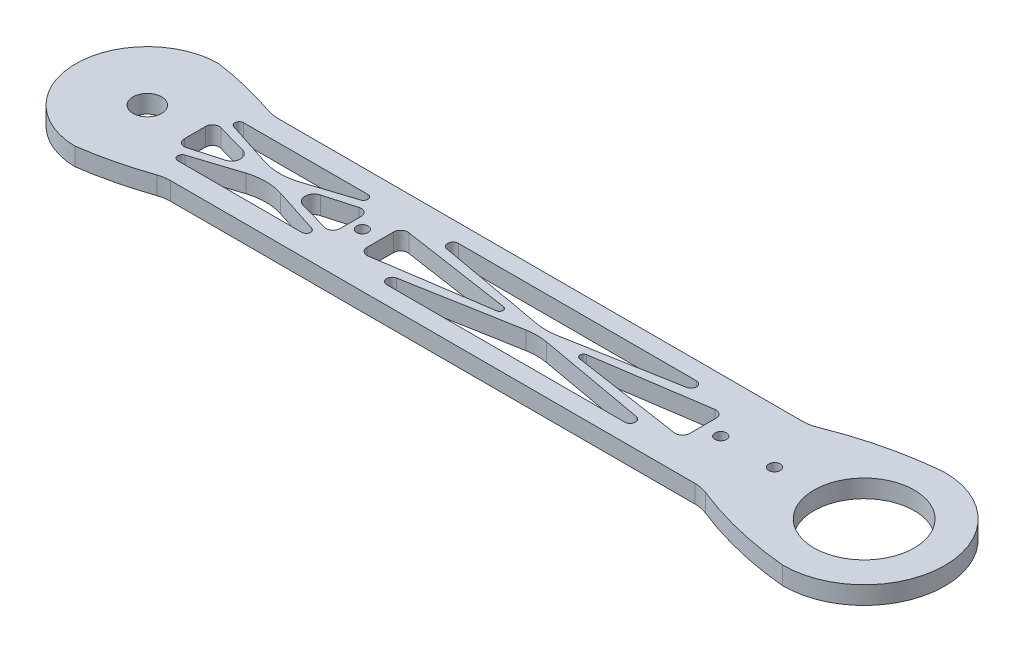
SolidWorks part; units mm, degrees
material "Thornel Mat VMA"
ref_plane "前视基准面" through (0, 0, 0) normal (0, 0, 1) x (1, 0, 0)
ref_plane "上视基准面" through (0, 0, 0) normal (0, 1, 0) x (1, 0, 0)
ref_plane "右视基准面" through (0, 0, 0) normal (1, 0, 0) x (0, 0, -1)
sketch "草图1" plane through (0, 0, 0) normal (0, 1, 0) x (1, 0, 0)
  line L0 (-0.25, 19.9984) -> (199.7188, 22.4982)
  line L5 (300, 0) -> (-49700, 0) construction
  line L6 (-0.25, -19.9984) -> (199.7188, -22.4982)
  arc A0 (-0.25, 19.9984) -> (-0.25, -19.9984) centre (0, 0) ccw
  arc A1 (199.7188, -22.4982) -> (199.7188, 22.4982) centre (200, 0) ccw
  point P0 (0, 0)
  dimension "D1" = 40
  dimension "D2" = 45
  dimension "D3" = 200
extrude "凸台-拉伸1" add sketch "草图1" along normal blind 5
sketch "草图2" plane through (0, 5, 0) normal (0, 1, 0) x (1, 0, 0)
  circle A0 centre (0, 0) radius 4
  dimension "D1" = 8
extrude "切除-拉伸1" cut sketch "草图2" against normal blind 6
sketch "草图3" plane through (0, 5, 0) normal (0, 1, 0) x (1, 0, 0)
  circle A0 centre (200, 0) radius 14
  dimension "D1" = 28
extrude "切除-拉伸2" cut sketch "草图3" against normal blind 10
sketch "草图4" plane through (0, 5, 0) normal (0, 1, 0) x (1, 0, 0)
  line L0 (0, 0) -> (0, 50000) construction
  circle A0 centre (0, 0) radius 12 construction
  circle A1 centre (0, 12) radius 2.1
  circle A2 centre (10.3923, 6) radius 2.1
  circle A3 centre (10.3923, -6) radius 2.1
  circle A4 centre (0, -12) radius 2.1
  circle A5 centre (-10.3923, -6) radius 2.1
  circle A6 centre (-10.3923, 6) radius 2.1
  point P15 (0, 0)
  point P27 (0, 0)
  dimension "D1" = 24
  dimension "D2" = 4.2
  dimension "D3" = 6
sketch "草图6" plane through (0, 5, 0) normal (0, 1, 0) x (1, 0, 0)
  line L0 (60, 15) -> (160.4981, 9.9876)
  line L1 (60, -15) -> (160.4981, -9.9876)
  arc A0 (60, 15) -> (60, -15) centre (60, 0) ccw
  arc A1 (160.4981, -9.9876) -> (160.4981, 9.9876) centre (160, 0) ccw
  dimension "D3" = 30
  dimension "D4" = 20
  dimension "D1" = 100
  dimension "D2" = 60
sketch "草图8" plane through (0, 5, 0) normal (0, 1, 0) x (1, 0, 0)
  line L0 (-0.25, 11.9978) -> (199.7188, 14.4976) construction
  line L1 (199.7188, 22.4982) -> (-0.25, 19.9984) construction
  line L2 (0, 0) -> (50000, 0) construction
  circle A0 centre (65, 12.8135) radius 1.6
  circle A2 centre (114.8261, 8.6468) radius 1.6
  circle A3 centre (164.6522, 4.4802) radius 1.6
  circle A6 centre (164.6522, -4.4802) radius 1.6
  circle A7 centre (114.8261, -8.6468) radius 1.6
  circle A8 centre (65, -12.8135) radius 1.6
  dimension "D2" = 3.2
  dimension "D1" = 8
  dimension "D3" = 65
  dimension "D4" = 3
  dimension "D5" = 50
sketch "草图10" plane through (0, 5, 0) normal (0, 1, 0) x (1, 0, 0)
  line L1 (19.75, 15) -> (169.7188, 15)
  line L2 (19.75, 15) -> (19.75, -15) construction
  line L3 (19.75, -15) -> (169.7188, -15)
  line L4 (169.7188, 15) -> (169.7188, -15) construction
  line L5 (19.75, 15) -> (169.7188, -15) construction
  line L6 (19.75, -15) -> (169.7188, 15) construction
  line L8 (-0.25, 19.9984) -> (199.7188, 22.4982)
  line L9 (-0.25, -19.9984) -> (199.7188, -22.4982)
  arc A0 (-0.25, 19.9984) -> (19.75, 15) centre (-14.3673, -79.0001) cw
  arc A1 (-0.25, -19.9984) -> (19.75, -15) centre (-14.3673, 79.0001) ccw
  arc A2 (199.7188, 22.4982) -> (169.7188, 15) centre (208.6754, -77.0998) ccw
  arc A3 (199.7188, -22.4982) -> (169.7188, -15) centre (208.6754, 77.0998) cw
  point P0 (94.7344, 0)
  dimension "D4" = 100
  dimension "D5" = 100
  dimension "D6" = 100
  dimension "D7" = 100
  dimension "D1" = 30
  dimension "D2" = 20
  dimension "D3" = 30
extrude "切除-拉伸4" cut sketch "草图10" against normal through all
fillet "圆角1" radius 10 4 edges at (169.7188, 2.5, -15) (169.7188, 2.5, 15) (19.75, 2.5, 15) (19.75, 2.5, -15)
sketch "草图11" plane through (0, 5, 0) normal (0, 1, 0) x (1, 0, 0)
  line L0 (167.741, -15) -> (21.4655, -15) construction
  line L1 (65, -10) -> (155, -10) construction
  line L2 (65, -10) -> (65, 10) construction
  line L3 (65, 10) -> (155, 10) construction
  line L4 (155, -10) -> (155, 10) construction
  line L5 (21.4655, 15) -> (167.741, 15) construction
  line L6 (105, 0) -> (65, -6) construction
  line L7 (105, 0) -> (65, 6) construction
  line L8 (65, 0) -> (155, 0) construction
  line L9 (110, 10) -> (110, -10) construction
  line L10 (42.8036, 10) -> (177.1964, 10) construction
  line L11 (60, 10) -> (110, 1) construction
  line L12 (110, 1) -> (160, 10) construction
  line L13 (76.8006, 10) -> (143.1994, 10)
  line L14 (65, 3.6776) -> (65, -3.6776)
  line L15 (76.5349, 7.0237) -> (107.1656, 1.5102)
  line L16 (112.8344, 1.5102) -> (143.4651, 7.0237)
  line L17 (67.2967, -5.6555) -> (98.4071, -0.9889)
  line L18 (67.2967, 5.6555) -> (98.4071, 0.9889)
  line L19 (155, 3.6776) -> (155, -3.6776)
  line L20 (152.7033, -5.6555) -> (121.5929, -0.9889)
  line L21 (152.7033, 5.6555) -> (121.5929, 0.9889)
  line L22 (76.5349, -7.0237) -> (107.1656, -1.5102)
  line L23 (76.8006, -10) -> (143.1994, -10)
  line L24 (112.8344, -1.5102) -> (143.4651, -7.0237)
  circle A0 centre (160, 0) radius 1.6
  circle A1 centre (60, 0) radius 1.6
  circle A2 centre (200, 0) radius 14 construction
  arc A3 (65, 3.6776) -> (67.2967, 5.6555) centre (67, 3.6776) cw
  arc A4 (98.4071, 0.9889) -> (98.4071, -0.9889) centre (98.2588, 0) cw
  arc A5 (65, -3.6776) -> (67.2967, -5.6555) centre (67, -3.6776) ccw
  arc A6 (76.8006, 10) -> (76.5349, 7.0237) centre (76.8006, 8.5) ccw
  arc A7 (107.1656, 1.5102) -> (112.8344, 1.5102) centre (110, 17.2571) ccw
  arc A8 (143.1994, 10) -> (143.4651, 7.0237) centre (143.1994, 8.5) cw
  arc A9 (155, 3.6776) -> (152.7033, 5.6555) centre (153, 3.6776) ccw
  arc A10 (155, -3.6776) -> (152.7033, -5.6555) centre (153, -3.6776) cw
  arc A11 (121.5929, 0.9889) -> (121.5929, -0.9889) centre (121.7412, 0) ccw
  arc A12 (107.1656, -1.5102) -> (112.8344, -1.5102) centre (110, -17.2571) cw
  arc A13 (76.8006, -10) -> (76.5349, -7.0237) centre (76.8006, -8.5) cw
  arc A14 (143.1994, -10) -> (143.4651, -7.0237) centre (143.1994, -8.5) ccw
  circle A15 centre (175, 0) radius 1.6
  point P18 (110, 0)
  point P21 (110, 0)
  point P28 (110, 10)
  dimension "D1" = 3.2
  dimension "D2" = 3.2
  dimension "D3" = 40
  dimension "D15" = 2
  dimension "D16" = 1
  dimension "D17" = 1.5
  dimension "D18" = 16
  dimension "D19" = 3.2
  dimension "D4" = 100
  dimension "D5" = 5
  dimension "D6" = 5
  dimension "D7" = 5
  dimension "D8" = 5
  dimension "D9" = 12
  dimension "D10" = 4
  dimension "D11" = 5
  dimension "D12" = 1
  dimension "D13" = 100
  dimension "D14" = 50
  dimension "D20" = 15
extrude "切除-拉伸5" cut sketch "草图11" against normal through all
sketch "草图12" plane through (0, 5, 0) normal (0, 1, 0) x (1, 0, 0)
  line L0 (13.2791, -9.1905) -> (56.7209, -9.1905) construction
  line L1 (13.2791, -9.1905) -> (13.2791, 9.1905) construction
  line L2 (13.2791, 9.1905) -> (56.7209, 9.1905) construction
  line L3 (56.7209, -9.1905) -> (56.7209, 9.1905) construction
  line L4 (32.7417, 0) -> (13.2791, -5.5043) construction
  line L5 (32.7417, 0) -> (13.2791, 5.5043) construction
  line L6 (13.2791, 0) -> (56.7209, 0) construction
  line L7 (35, 9.1905) -> (35, -9.1905) construction
  line L8 (-32.3228, 9.1905) -> (102.3228, 9.1905) construction
  line L9 (9.9874, 9.1905) -> (35, 1.1136) construction
  line L10 (35, 1.1136) -> (60.0126, 9.1905) construction
  line L11 (17.6866, 9.1905) -> (52.3134, 9.1905)
  line L12 (13.2791, 2.9674) -> (13.2791, -2.9674)
  line L13 (17.3141, 6.8246) -> (30.1704, 2.6732)
  line L14 (39.8296, 2.6732) -> (52.6859, 6.8246)
  line L15 (15.7201, -4.8139) -> (24.1739, -2.4231)
  line L16 (15.7201, 4.8139) -> (24.1739, 2.4231)
  line L17 (56.7209, 2.9674) -> (56.7209, -2.9674)
  line L18 (54.2799, -4.8139) -> (45.8261, -2.4231)
  line L19 (54.2799, 4.8139) -> (45.8261, 2.4231)
  line L20 (17.3141, -6.8246) -> (30.1704, -2.6732)
  line L21 (17.6866, -9.1905) -> (52.3134, -9.1905)
  line L22 (39.8296, -2.6732) -> (52.6859, -6.8246)
  arc A2 (13.2791, 2.9674) -> (15.7201, 4.8139) centre (15.1979, 2.9674) cw
  arc A3 (24.1739, 2.4231) -> (24.1739, -2.4231) centre (23.4886, 0) cw
  arc A4 (13.2791, -2.9674) -> (15.7201, -4.8139) centre (15.1979, -2.9674) ccw
  arc A5 (17.6866, 9.1905) -> (17.3141, 6.8246) centre (17.6866, 7.9782) ccw
  arc A6 (30.1704, 2.6732) -> (39.8296, 2.6732) centre (35, 17.6297) ccw
  arc A7 (52.3134, 9.1905) -> (52.6859, 6.8246) centre (52.3134, 7.9782) cw
  arc A8 (56.7209, 2.9674) -> (54.2799, 4.8139) centre (54.8021, 2.9674) ccw
  arc A9 (56.7209, -2.9674) -> (54.2799, -4.8139) centre (54.8021, -2.9674) cw
  arc A10 (45.8261, 2.4231) -> (45.8261, -2.4231) centre (46.5114, 0) ccw
  arc A11 (30.1704, -2.6732) -> (39.8296, -2.6732) centre (35, -17.6297) cw
  arc A12 (17.6866, -9.1905) -> (17.3141, -6.8246) centre (17.6866, -7.9782) cw
  arc A13 (52.3134, -9.1905) -> (52.6859, -6.8246) centre (52.3134, -7.9782) ccw
  point P0 (35, 0)
  point P3 (35, 0)
  point P15 (35, 0)
  point P18 (35, 0)
  point P25 (35, 9.1905)
  dimension "D1" = 35
extrude "切除-拉伸6" cut sketch "草图12" against normal blind 10
